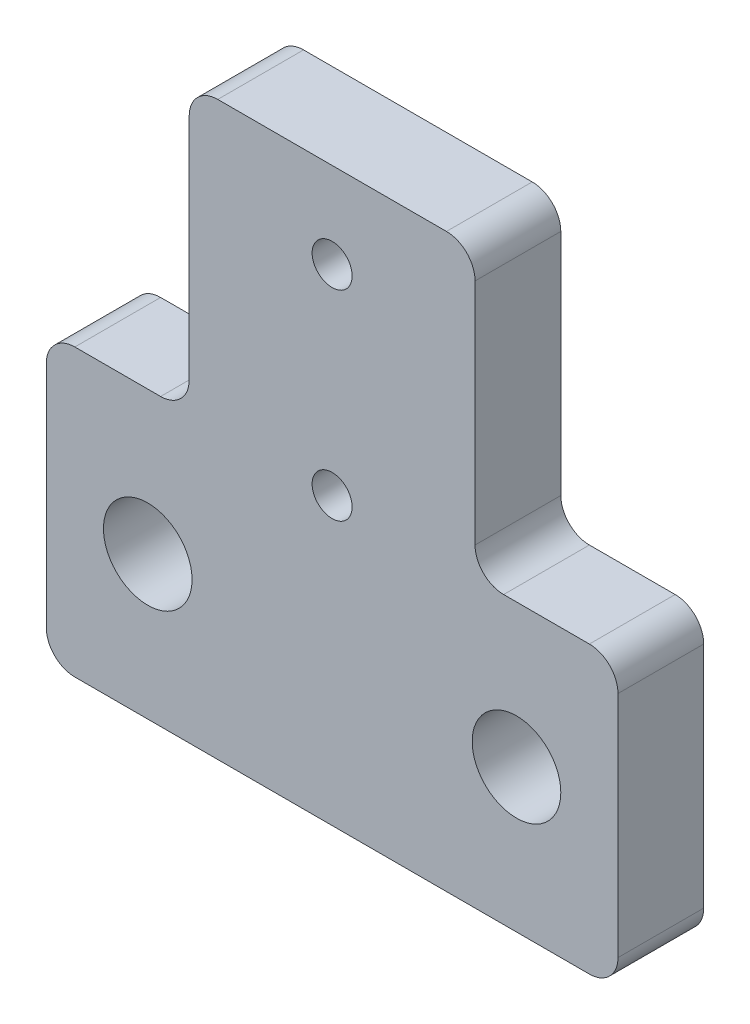
SolidWorks part; units mm, degrees
ref_plane "前视基准面" through (0, 0, 0) normal (0, 0, 1) x (1, 0, 0)
ref_plane "上视基准面" through (0, 0, 0) normal (0, 1, 0) x (1, 0, 0)
ref_plane "右视基准面" through (0, 0, 0) normal (1, 0, 0) x (0, 0, -1)
sketch "草图1" plane through (0, 0, 0) normal (0, 0, 1) x (1, 0, 0)
  line L0 (-4.3522, -10) -> (-4.3522, 0) construction
  line L1 (-5, 10) -> (5, 10)
  line L2 (-5, 10) -> (-5, 0)
  line L3 (-5, -10) -> (5, -10)
  line L4 (5, 10) -> (5, 0)
  line L5 (-5, 10) -> (5, -10) construction
  line L6 (-5, -10) -> (5, 10) construction
  line L7 (-8, -5) -> (-10, -5) construction
  line L8 (-5, 0) -> (-10, 0)
  line L10 (-5, -10) -> (-10, -10)
  line L11 (-10, 0) -> (-10, -10)
  line L12 (5, 0) -> (10, 0)
  line L14 (5, -10) -> (10, -10)
  line L15 (10, 0) -> (10, -10)
  line L16 (10, -5) -> (8, -5) construction
  line L19 (-5, 6.1484) -> (0, 6.1484) construction
  line L20 (0, 10) -> (0, 7) construction
  line L21 (0, 7) -> (0, 0) construction
  circle A0 centre (-6.45, -5) radius 1.55
  circle A1 centre (6.45, -5) radius 1.55
  circle A2 centre (0, 0) radius 0.7
  circle A3 centre (0, 7) radius 0.7
  point P0 (0, 0)
  dimension "D6" = 3.1
  dimension "D7" = 3.1
  dimension "D12" = 1.4
  dimension "D13" = 1.4
  dimension "D1" = 10
  dimension "D2" = 20
  dimension "D3" = 10
  dimension "D4" = 5
  dimension "D5" = 5
  dimension "D8" = 2
  dimension "D9" = 2
  dimension "D10" = 3
  dimension "D11" = 7
extrude "凸台-拉伸1" add sketch "草图1" along normal blind 3
fillet "圆角1" radius 1 8 edges at (-5, 0, 1.5) (5, 0, 1.5) (10, 0, 1.5) (10, -10, 1.5) (-10, -10, 1.5) (-10, 0, 1.5) (5, 10, 1.5) (-5, 10, 1.5)
